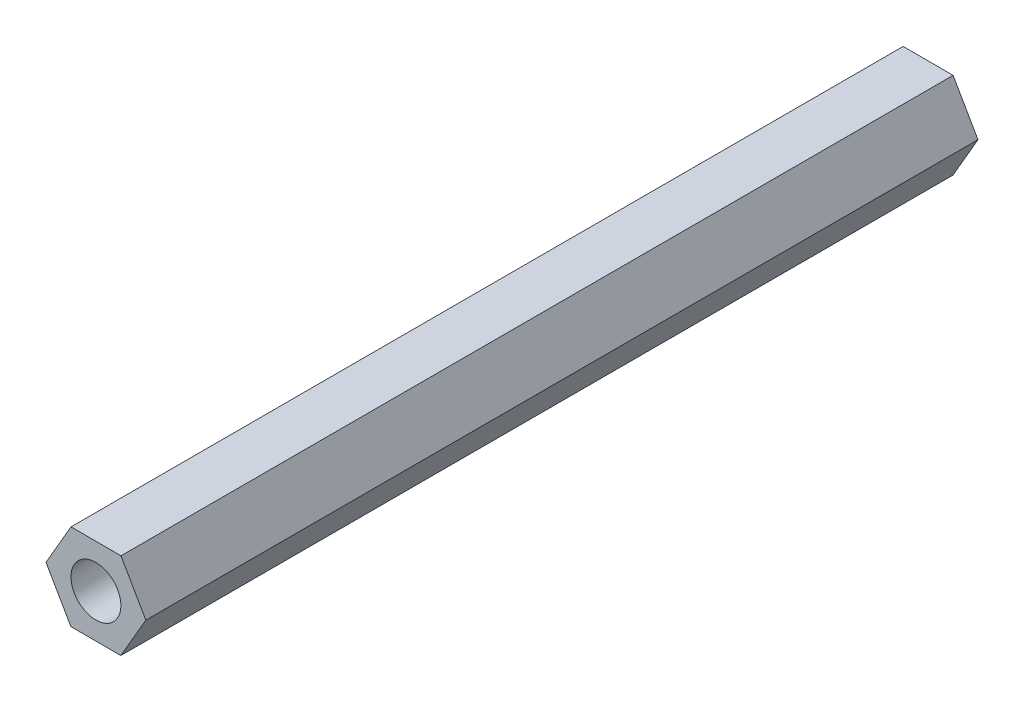
SolidWorks part; units mm, degrees
ref_plane "前视基准面" through (0, 0, 0) normal (0, 0, 1) x (1, 0, 0)
ref_plane "上视基准面" through (0, 0, 0) normal (0, 1, 0) x (1, 0, 0)
ref_plane "右视基准面" through (0, 0, 0) normal (1, 0, 0) x (0, 0, -1)
ref_plane "基准面1" through (0, 0, 0) normal (0, -1, 0) x (1, 0, 0)
sketch "草图1" plane through (0, 0, 0) normal (0, -1, 0) x (1, 0, 0)
  line L0 (2.5, 50) -> (1.5, 50)
  line L1 (1.5, 50) -> (1.5, 0)
  line L2 (1.5, 0) -> (2.5, 0)
  line L3 (2.5, 0) -> (2.5, 50)
  line L4 (0, 50) -> (0, 0) construction
revolve "旋转1" add sketch "草图1" angle 360 about L4
sketch "草图5" plane through (0, 0, 0) normal (0, 0, -1) x (-1, 0, 0)
  line L1 (-1.5042, 2.5956) -> (-3, -0.0049)
  line L2 (-3, -0.0049) -> (-1.4958, -2.6005)
  line L3 (-1.4958, -2.6005) -> (1.5042, -2.5956)
  line L4 (1.5042, -2.5956) -> (3, 0.0049)
  line L5 (3, 0.0049) -> (1.4958, 2.6005)
  line L6 (1.4958, 2.6005) -> (-1.5042, 2.5956)
  circle A0 centre (0, 0) radius 2.5981 construction
  circle A1 centre (0, 0) radius 1.5
  dimension "D1" = 3
  dimension "D2" = 3
extrude "凸台-拉伸4" add sketch "草图5" against normal blind 50
